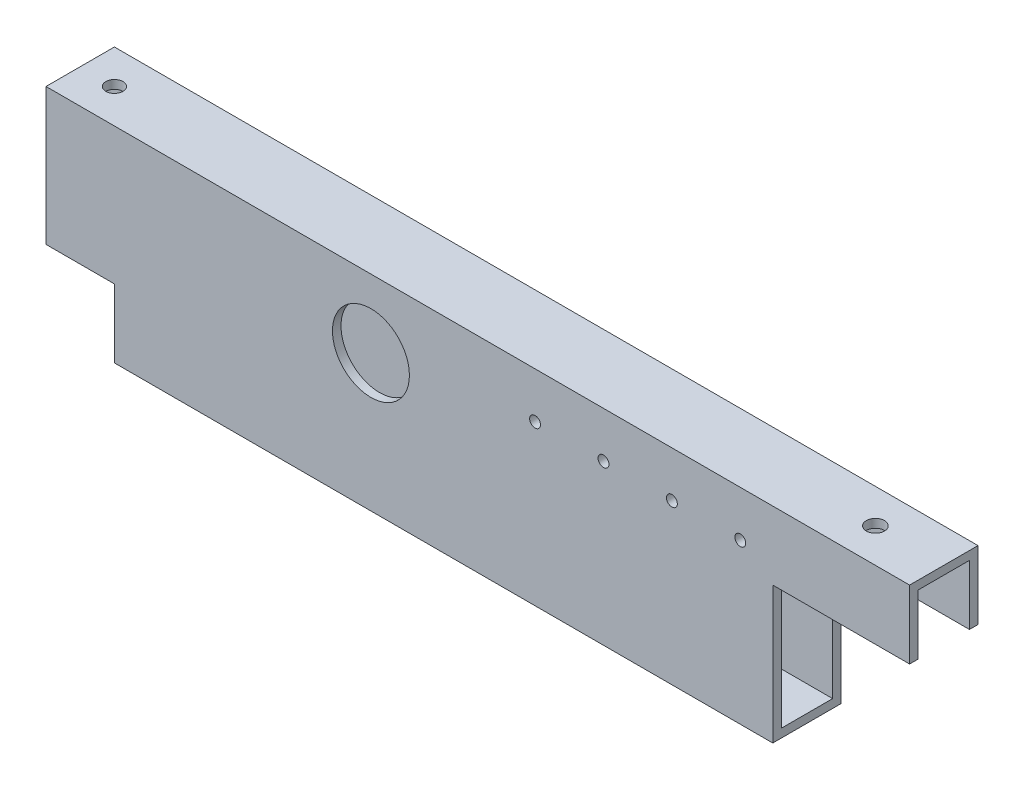
SolidWorks part; units mm, degrees
material "6061-T6 (SS)"
ref_plane "Front Plane" through (0, 0, 0) normal (0, 0, 1) x (1, 0, 0)
ref_plane "Top Plane" through (0, 0, 0) normal (0, 1, 0) x (1, 0, 0)
ref_plane "Right Plane" through (0, 0, 0) normal (1, 0, 0) x (0, 0, -1)
sketch "Sketch1" plane through (0, 0, 0) normal (0, 0, 1) x (1, 0, 0)
  line L0 (-288.925, -12.7) -> (-263.525, -12.7)
  line L1 (-288.925, 38.1) -> (288.925, 38.1)
  line L2 (-288.925, 38.1) -> (-288.925, -38.1)
  line L3 (-288.925, -38.1) -> (288.925, -38.1)
  line L4 (288.925, 38.1) -> (288.925, -38.1)
  line L5 (-288.925, 38.1) -> (288.925, -38.1) construction
  line L6 (-288.925, -38.1) -> (288.925, 38.1) construction
  line L7 (-288.925, -38.1) -> (-282.575, -38.1) construction
  line L8 (-288.925, -38.1) -> (-288.925, -31.75) construction
  line L9 (-288.925, -31.75) -> (-282.575, -31.75) construction
  line L10 (-282.575, -38.1) -> (-282.575, -31.75) construction
  line L11 (288.925, -38.1) -> (277.3518, -38.1) construction
  line L12 (288.925, -38.1) -> (288.925, -26.5268) construction
  line L13 (288.925, -26.5268) -> (277.3518, -26.5268) construction
  line L14 (277.3518, -38.1) -> (277.3518, -26.5268) construction
  line L15 (-263.525, -12.7) -> (-263.525, -38.1)
  line L16 (263.525, -38.1) -> (263.525, -12.7)
  line L17 (263.525, -12.7) -> (288.925, -12.7)
  point P0 (0, 0)
  dimension "D1" = 577.85
  dimension "D2" = 76.2
  dimension "D3" = 6.35
  dimension "D4" = 25.4
  dimension "D5" = 25.4
extrude "Boss-Extrude1" add sketch "Sketch1" along normal mid plane 25.4 contours L3 L14 L13 L4 L1 L2 L9 L10
hole_wizard "1/4 (0.25) Diameter Hole1" positions "Sketch4" profile "Sketch3" hole size "1/4" standard "ANSI Inch" end condition through all
sketch "Sketch4" plane through (0, 38.1, 0) normal (0, 1, 0) x (1, 0, 0)
  line L0 (-288.925, -12.7) -> (-288.925, 12.7) construction
  line L1 (288.925, -12.7) -> (288.925, 12.7) construction
  point P0 (-276.225, 0)
  point P2 (276.225, 0)
  point P5 (-288.925, 0)
  dimension "D1" = 12.7
  dimension "D2" = 12.7
sketch "Sketch3" plane through (-276.225, 38.1, 0) normal (1, 0, 0) x (0, 0, 1)
  line L0 (0, 0) -> (0, 76.2)
  line L1 (0, 76.2) -> (3.175, 76.2)
  line L2 (3.175, 76.2) -> (3.175, 0)
  line L5 (3.175, 0) -> (0, 0)
  line L11 (0, -6.35) -> (0, 107.95) construction
  dimension "Thru Hole Dia." = 6.35
  dimension "Thru Hole Depth" = 76.2
sketch "Sketch5" plane through (288.925, 0, 0) normal (1, 0, 0) x (0, 0, -1)
  line L27 (9.525, -12.7) -> (9.525, 34.925)
  line L28 (9.525, -34.925) -> (9.525, -12.7)
  line L29 (-9.525, -12.7) -> (-9.525, -34.925)
  line L30 (-9.525, -34.925) -> (9.525, -34.925)
  line L31 (-9.525, 34.925) -> (-9.525, -12.7)
  line L32 (9.525, 34.925) -> (-9.525, 34.925)
  line L33 (9.525, -12.7) -> (9.525, 34.925)
  line L34 (9.525, -34.925) -> (9.525, -12.7)
  line L35 (-9.525, -12.7) -> (-9.525, -34.925)
  line L36 (-9.525, -34.925) -> (9.525, -34.925)
  line L37 (-9.525, 34.925) -> (-9.525, -12.7)
  line L38 (9.525, 34.925) -> (-9.525, 34.925)
  dimension "D1" = 3.175
extrude "Cut-Extrude1" cut sketch "Sketch5" against normal through all
sketch "Sketch8" plane through (0, 0, 12.7) normal (0, 0, 1) x (1, 0, 0)
  line L0 (-288.925, 38.1) -> (288.925, 38.1) construction
  line L1 (-288.925, 38.1) -> (-288.925, -12.7) construction
  line L2 (288.925, 38.1) -> (288.925, -12.7) construction
  circle A0 centre (-168.275, 12.7) radius 14.2875
  circle A1 centre (168.275, 12.7) radius 14.2875
  dimension "D1" = 25.4
  dimension "D2" = 28.575
  dimension "D3" = 120.65
  dimension "D4" = 25.4
  dimension "D5" = 120.65
extrude "Cut-Extrude2" cut sketch "Sketch8" against normal through all
hole_wizard "#10-32 Tapped Hole1" positions "Sketch10" profile "Sketch9" tap size "#10-32" standard "ANSI Inch"
sketch "Sketch10" plane through (0, 0, 12.7) normal (0, 0, 1) x (1, 0, 0)
  line L0 (-288.925, 38.1) -> (-288.925, -12.7) construction
  line L1 (-288.925, 38.1) -> (288.925, 38.1) construction
  point P0 (-107.315, 21.082)
  point P8 (-81.915, 21.082)
  point P9 (-56.515, 21.082)
  point P10 (-31.115, 21.082)
  dimension "D1" = 181.61
  dimension "D3" = 17.018
  dimension "D2" = 4
sketch "Sketch9" plane through (-107.315, 21.082, 12.7) normal (1, 0, 0) x (0, -1, 0)
  line L0 (0, 0) -> (0, 14.9293)
  line L1 (0, 14.9293) -> (2.0193, 13.716)
  line L2 (2.0193, 13.716) -> (2.0193, 0)
  line L5 (2.0193, 0) -> (0, 0)
  line L10 (0, 14.9293) -> (-2.0193, 13.716) construction
  line L11 (0, -6.35) -> (0, 107.95) construction
  dimension "Tap Drill Dia." = 4.0386
  dimension "Tap Drill Depth" = 13.716
  dimension "Drill Angle" = 118
cosmetic thread "Hole Thread1" parameters "D1"=3.175, "D2"=4.826
cosmetic thread "Hole Thread2" parameters "D1"=3.175, "D2"=4.826
cosmetic thread "Hole Thread3" parameters "D1"=3.175, "D2"=4.826
cosmetic thread "Hole Thread4" parameters "D1"=3.175, "D2"=4.826
sketch "Sketch11" plane through (0, 0, 12.7) normal (0, 0, 1) x (1, 0, 0)
  line L0 (-263.525, -38.1) -> (263.525, -38.1) construction
  line L1 (288.925, 38.1) -> (31.75, 38.1)
  line L2 (288.925, 38.1) -> (288.925, -38.1)
  line L3 (288.925, -38.1) -> (31.75, -38.1)
  line L4 (31.75, 38.1) -> (31.75, -38.1)
  dimension "D1" = 257.175
extrude "Cut-Extrude3" cut sketch "Sketch11" against normal through all
sketch "Sketch13" plane through (0, 0, 12.7) normal (0, 0, 1) x (1, 0, 0)
  line L1 (31.75, -38.1) -> (-19.05, -38.1)
  line L2 (31.75, -38.1) -> (31.75, 12.7)
  line L3 (31.75, 12.7) -> (-19.05, 12.7)
  line L4 (-19.05, -38.1) -> (-19.05, 12.7)
  dimension "D1" = 50.8
  dimension "D2" = 50.8
extrude "Cut-Extrude5" cut sketch "Sketch13" against normal through all
hole_wizard "1/4 Clearance Hole1" positions "Sketch16" profile "Sketch14" hole size "1/4" standard "ANSI Inch" end condition through all
sketch "Sketch16" plane through (0, 38.1, 0) normal (0, 1, 0) x (1, 0, 0)
  line L0 (31.75, 12.7) -> (31.75, -12.7) construction
  point P0 (6.35, 0)
  dimension "D1" = 25.4
sketch "Sketch14" plane through (6.35, 38.1, 0) normal (1, 0, 0) x (0, 0, 1)
  line L0 (0, 0) -> (0, 76.2)
  line L1 (0, 76.2) -> (3.3782, 76.2)
  line L2 (3.3782, 76.2) -> (3.3782, 0)
  line L5 (3.3782, 0) -> (0, 0)
  line L11 (0, -6.35) -> (0, 107.95) construction
  dimension "Thru Hole Dia." = 6.7564
  dimension "Thru Hole Depth" = 76.2
